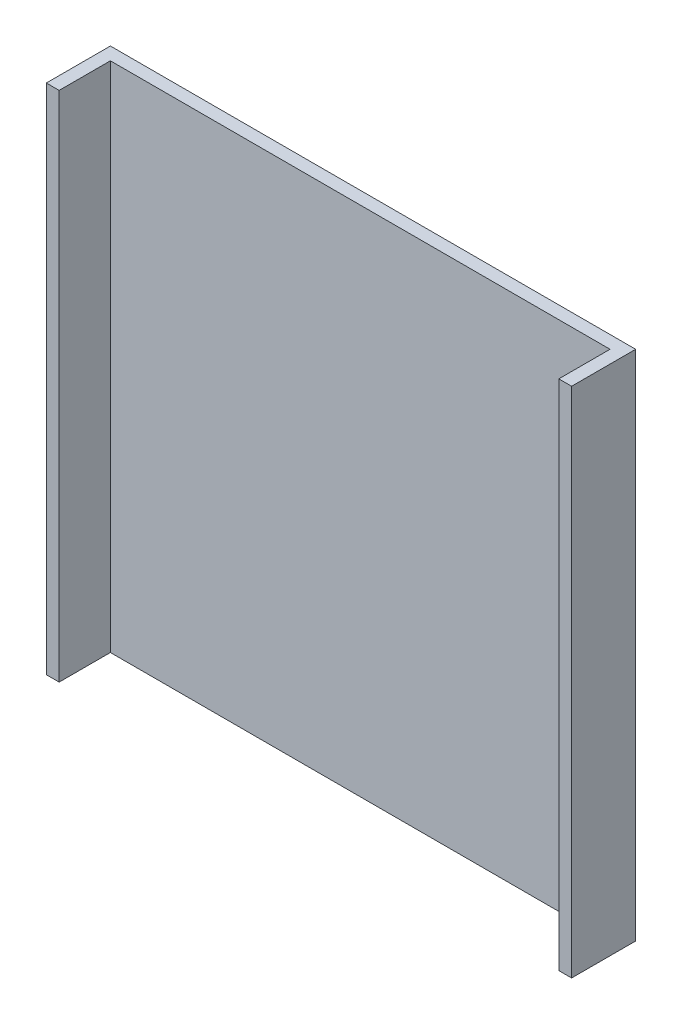
SolidWorks part; units mm, degrees
ref_plane "Front Plane" through (0, 0, 0) normal (0, 0, 1) x (1, 0, 0)
ref_plane "Top Plane" through (0, 0, 0) normal (0, 1, 0) x (1, 0, 0)
ref_plane "Right Plane" through (0, 0, 0) normal (1, 0, 0) x (0, 0, -1)
sketch "Sketch1" plane through (0, 0, 0) normal (0, 0, 1) x (1, 0, 0)
  line L1 (0, 0) -> (260.35, 0)
  line L2 (0, 0) -> (0, 254)
  line L3 (0, 254) -> (260.35, 254)
  line L4 (260.35, 0) -> (260.35, 254)
  dimension "D1" = 260.35
  dimension "D2" = 254
extrude "Boss-Extrude1" add sketch "Sketch1" along normal blind 6.35
sketch "Sketch2" plane through (0, 0, 6.35) normal (0, 0, 1) x (1, 0, 0)
  line L0 (0, 0) -> (260.35, 0) construction
  line L1 (0, 254) -> (6.35, 254)
  line L2 (0, 254) -> (0, 0)
  line L3 (0, 0) -> (6.35, 0)
  line L4 (6.35, 254) -> (6.35, 0)
  dimension "D1" = 6.35
extrude "Boss-Extrude2" add sketch "Sketch2" along normal blind 25.4
sketch "Sketch5" plane through (0, 0, 6.35) normal (0, 0, 1) x (1, 0, 0)
  line L0 (6.35, 0) -> (260.35, 0) construction
  line L1 (260.35, 254) -> (254, 254)
  line L2 (260.35, 254) -> (260.35, 0)
  line L3 (260.35, 0) -> (254, 0)
  line L4 (254, 254) -> (254, 0)
  dimension "D1" = 6.35
extrude "Boss-Extrude4" add sketch "Sketch5" along normal blind 25.4
sketch "Sketch6" plane through (0, 0, 0) normal (0, 0, -1) x (-1, 0, 0)
  line L0 (-260.35, 254) -> (0, 0) construction
  circle A0 centre (-130.175, 127) radius 45.1274 construction
